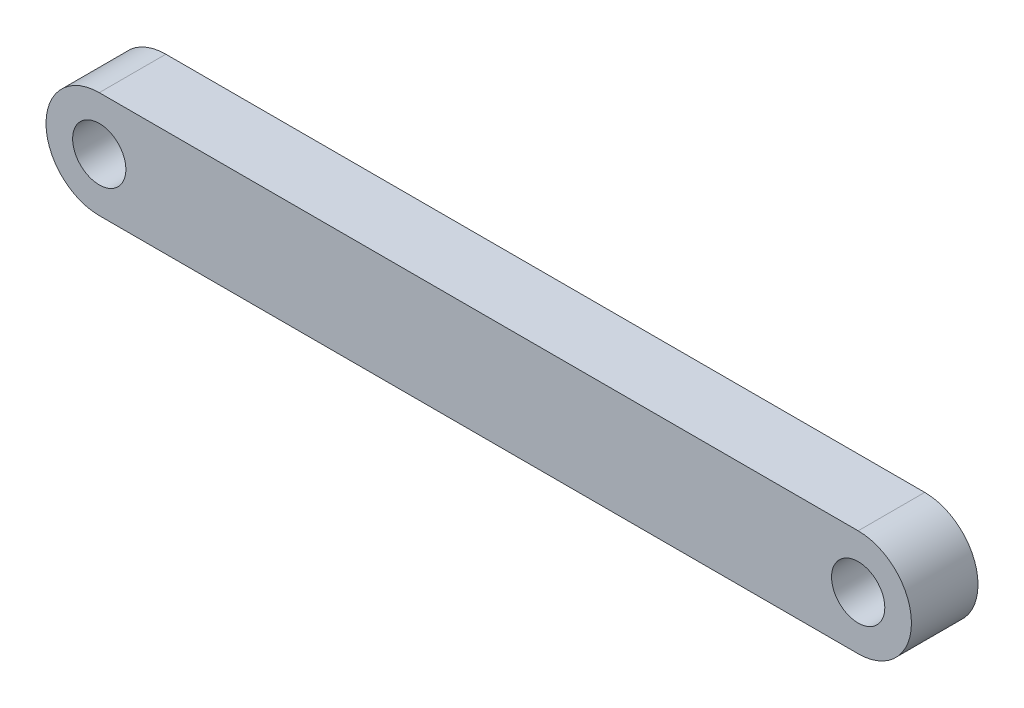
SolidWorks part; units mm, degrees
ref_plane "Front Plane" through (0, 0, 0) normal (0, 0, 1) x (1, 0, 0)
ref_plane "Top Plane" through (0, 0, 0) normal (0, 1, 0) x (1, 0, 0)
ref_plane "Right Plane" through (0, 0, 0) normal (1, 0, 0) x (0, 0, -1)
sketch "Sketch1" plane through (0, 0, 0) normal (0, 0, 1) x (1, 0, 0)
  line L0 (0, 0) -> (57, 0) construction
  line L1 (0, 4) -> (57, 4)
  line L2 (0, -4) -> (57, -4)
  arc A0 (0, 4) -> (0, -4) centre (0, 0) ccw
  arc A1 (57, -4) -> (57, 4) centre (57, 0) ccw
  point P3 (28.5, 0)
  point P8 (0, 0)
  dimension "D2" = 4
  dimension "D1" = 57
extrude "Boss-Extrude1" add sketch "Sketch1" along normal mid plane 5
sketch "Sketch2" plane through (0, 0, 2.5) normal (0, 0, 1) x (1, 0, 0)
  circle A0 centre (57, 0) radius 2
  circle A1 centre (0, 0) radius 2
  dimension "D1" = 4
  dimension "D2" = 4
extrude "Cut-Extrude1" cut sketch "Sketch2" against normal through all
